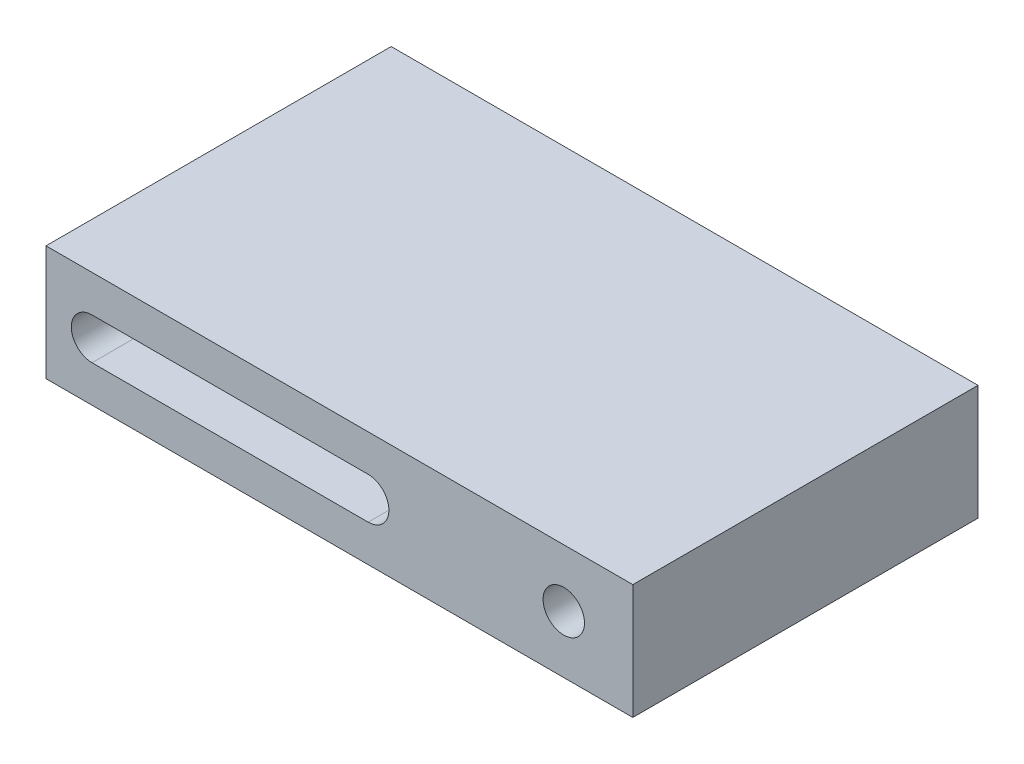
SolidWorks part; units mm, degrees
ref_plane "Front Plane" through (0, 0, 0) normal (0, 0, 1) x (1, 0, 0)
ref_plane "Top Plane" through (0, 0, 0) normal (0, 1, 0) x (1, 0, 0)
ref_plane "Right Plane" through (0, 0, 0) normal (1, 0, 0) x (0, 0, -1)
sketch "Sketch1" plane through (0, 0, 0) normal (0, 1, 0) x (1, 0, 0)
  line L1 (-1275, 750) -> (1275, 750)
  line L2 (-1275, 750) -> (-1275, -750)
  line L3 (-1275, -750) -> (1275, -750)
  line L4 (1275, 750) -> (1275, -750)
  line L5 (-1275, 750) -> (1275, -750) construction
  line L6 (-1275, -750) -> (1275, 750) construction
  point P0 (0, 0)
  dimension "D1" = 2550
  dimension "D2" = 1500
extrude "Boss-Extrude1" add sketch "Sketch1" along normal blind 500
sketch "Sketch2" plane through (0, 0, 750) normal (0, 0, 1) x (1, 0, 0)
  line L0 (-1275, 250) -> (1275, 250) construction
  line L1 (-1275, 500) -> (-1275, 0) construction
  line L2 (1275, 500) -> (1275, 0) construction
  line L3 (-1075, 250) -> (125, 250) construction
  line L4 (-1075, 340) -> (125, 340)
  line L5 (-1075, 160) -> (125, 160)
  arc A0 (-1075, 340) -> (-1075, 160) centre (-1075, 250) ccw
  arc A1 (125, 160) -> (125, 340) centre (125, 250) ccw
  circle A2 centre (975, 250) radius 90
  point P8 (-475, 250)
  dimension "D2" = 1200
  dimension "D3" = 200
  dimension "D4" = 180
  dimension "D5" = 300
  dimension "D1" = 180
extrude "Cut-Extrude1" cut sketch "Sketch2" against normal through all
